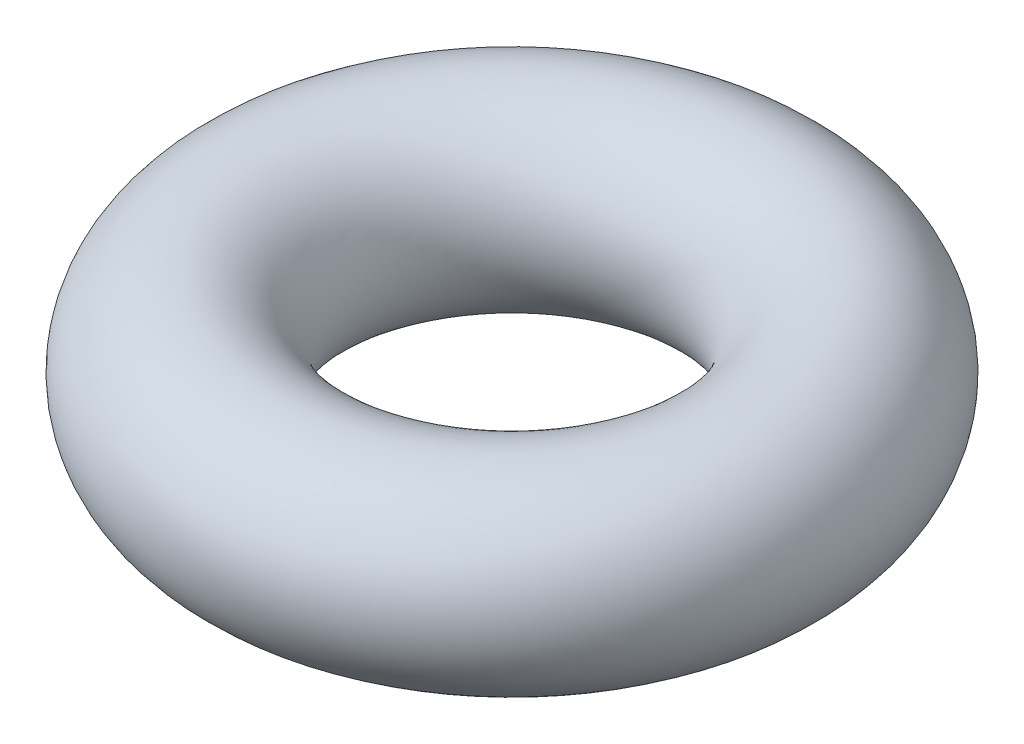
SolidWorks part; units mm, degrees
ref_plane "Front Plane" through (0, 0, 0) normal (0, 0, 1) x (1, 0, 0)
ref_plane "Top Plane" through (0, 0, 0) normal (0, 1, 0) x (1, 0, 0)
ref_plane "Right Plane" through (0, 0, 0) normal (1, 0, 0) x (0, 0, -1)
sketch "Sketch2" plane through (0, 0, 0) normal (0, 0, 1) x (1, 0, 0)
  line L0 (0, 75.9724) -> (0, -99.5686)
  circle A0 centre (-100, 0) radius 30
  dimension "D1" = 60
  dimension "D2" = 100
revolve "Revolve-Thin1" add sketch "Sketch2" angle 360 about L0
